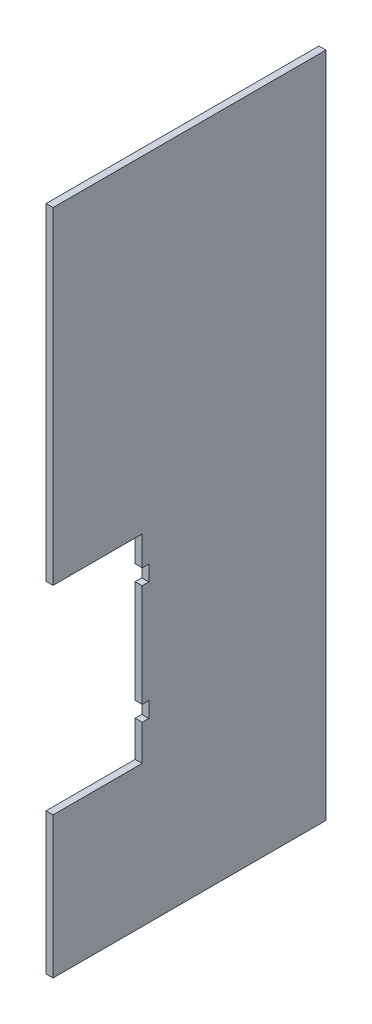
SolidWorks part; units mm, degrees
ref_plane "Спереди" through (0, 0, 0) normal (0, 0, 1) x (1, 0, 0)
ref_plane "Сверху" through (0, 0, 0) normal (0, 1, 0) x (1, 0, 0)
ref_plane "Справа" through (0, 0, 0) normal (1, 0, 0) x (0, 0, -1)
ref_plane "Плоскость4" through (0.5, 0, 0) normal (-1, 0, 0) x (0, -1, 0)
sketch "Эскиз1" plane through (0.5, 0, 0) normal (-1, 0, 0) x (0, -1, 0)
  line L0 (-5.85, 42.25) -> (-100.85, 42.25)
  line L1 (-100.85, 42.25) -> (-100.85, 3.4)
  line L2 (-100.85, 3.4) -> (-5.85, 3.4)
  line L3 (-5.85, 3.4) -> (-5.85, 42.25)
extrude "Бобышка-Вытянуть1" add sketch "Эскиз1" against normal blind 0.5
sketch "Эскиз2" plane through (0.5, 0, 0) normal (-1, 0, 0) x (0, 0, 1)
  line L0 (42.25, 5.85) -> (3.4, 5.85)
  line L1 (3.4, 5.85) -> (3.4, 100.85)
  line L2 (3.4, 100.85) -> (42.25, 100.85)
  line L3 (42.25, 100.85) -> (42.25, 5.85)
extrude "Бобышка-Вытянуть2" add sketch "Эскиз2" along normal blind 0.5
sketch "Эскиз3" plane through (0, 0, 0) normal (-1, 0, 0) x (0, 0, 1)
  line L1 (47.1872, 54.262) -> (29.5623, 54.262)
  line L2 (47.1872, 54.262) -> (47.1872, 25.9692)
  line L3 (47.1872, 25.9692) -> (29.5623, 25.9692)
  line L4 (29.5623, 54.262) -> (29.5623, 25.9692) construction
  line L5 (29.5623, 54.262) -> (29.5623, 50.0787)
  line L10 (29.5623, 50.0787) -> (28.6189, 50.0787)
  line L11 (28.6189, 50.0787) -> (28.6189, 47.8787)
  line L12 (28.6189, 47.8787) -> (29.5623, 47.8787)
  line L13 (29.5623, 47.8787) -> (29.5623, 33.2387)
  line L14 (29.5623, 33.2387) -> (28.6189, 33.2387)
  line L15 (28.6189, 33.2387) -> (28.6189, 31.0387)
  line L16 (28.6189, 31.0387) -> (29.5623, 31.0387)
  line L17 (29.5623, 31.0387) -> (29.5623, 25.9692)
  line L18 (28.9189, 49.7787) -> (31.0057, 49.7787) construction
  line L19 (28.9189, 48.1787) -> (28.9189, 49.7787) construction
  line L20 (31.0057, 48.1787) -> (28.9189, 48.1787) construction
  line L21 (28.9189, 32.9387) -> (31.0057, 32.9387) construction
  line L22 (28.9189, 31.3387) -> (28.9189, 32.9387) construction
  line L23 (31.0057, 31.3387) -> (28.9189, 31.3387) construction
  dimension "D1" = 0.3
  dimension "D2" = 0.3
  dimension "D3" = 0.3
  dimension "D4" = 0.3
  dimension "D5" = 0.3
  dimension "D6" = 0.3
extrude "Вырез-Вытянуть1" cut sketch "Эскиз3" against normal through all
